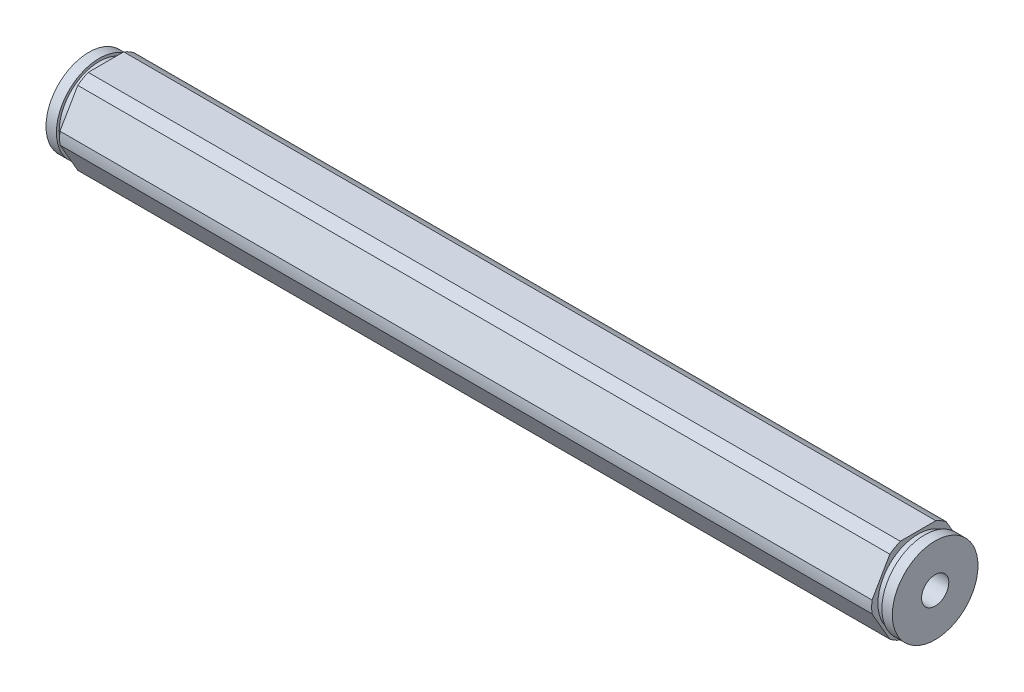
SolidWorks part; units mm, degrees
material "7075-T6 (SN)"
ref_plane "Front Plane" through (0, 0, 0) normal (0, 0, 1) x (1, 0, 0)
ref_plane "Top Plane" through (0, 0, 0) normal (0, 1, 0) x (1, 0, 0)
ref_plane "Right Plane" through (0, 0, 0) normal (1, 0, 0) x (0, 0, -1)
sketch "Sketch1" plane through (0, 0, 0) normal (1, 0, 0) x (0, 0, -1)
  line L1 (7.3323, 0) -> (3.6662, 6.35)
  line L2 (3.6662, 6.35) -> (-3.6662, 6.35)
  line L3 (-3.6662, 6.35) -> (-7.3323, 0)
  line L4 (-7.3323, 0) -> (-3.6662, -6.35)
  line L5 (-3.6662, -6.35) -> (3.6662, -6.35)
  line L6 (3.6662, -6.35) -> (7.3323, 0)
  circle A0 centre (0, 0) radius 6.35 construction
  dimension "D1" = 12.7
extrude "Boss-Extrude1" add sketch "Sketch1" along normal mid plane 125.476
sketch "Sketch2" plane through (0, 0, 0) normal (0, 1, 0) x (1, 0, 0)
  line L0 (60.198, -5.9436) -> (61.1886, -5.9436)
  line L1 (61.1886, -5.9436) -> (61.1886, -6.35)
  line L2 (61.1886, -6.35) -> (62.738, -6.35)
  line L3 (62.738, -6.35) -> (62.738, -8.89)
  line L4 (62.738, -8.89) -> (60.198, -8.89)
  line L5 (60.198, -8.89) -> (60.198, -5.9436)
  line L6 (0, 0) -> (49.5443, 0) construction
  point P4 (0, 0)
  dimension "D1" = 2.54
  dimension "D2" = 6.35
  dimension "D3" = 5.9436
  dimension "D4" = 2.54
  dimension "D5" = 0.9906
revolve "Cut-Revolve1" cut sketch "Sketch2" angle 360 about L6
mirror "Mirror1" about plane through (0, 0, 0) normal (1, 0, 0) of "Cut-Revolve1"
sketch "Sketch3" plane through (62.738, 0, 0) normal (1, 0, 0) x (0, 0, -1)
  circle A0 centre (0, 0) radius 6.875
  circle A1 centre (0, 0) radius 2.0193
  circle A2 centre (0, 0) radius 7.3323
  dimension "D1" = 4.0386
  dimension "D2" = 13.75
extrude "Cut-Extrude1" cut sketch "Sketch3" against normal through all contours A1 | A2 A0
